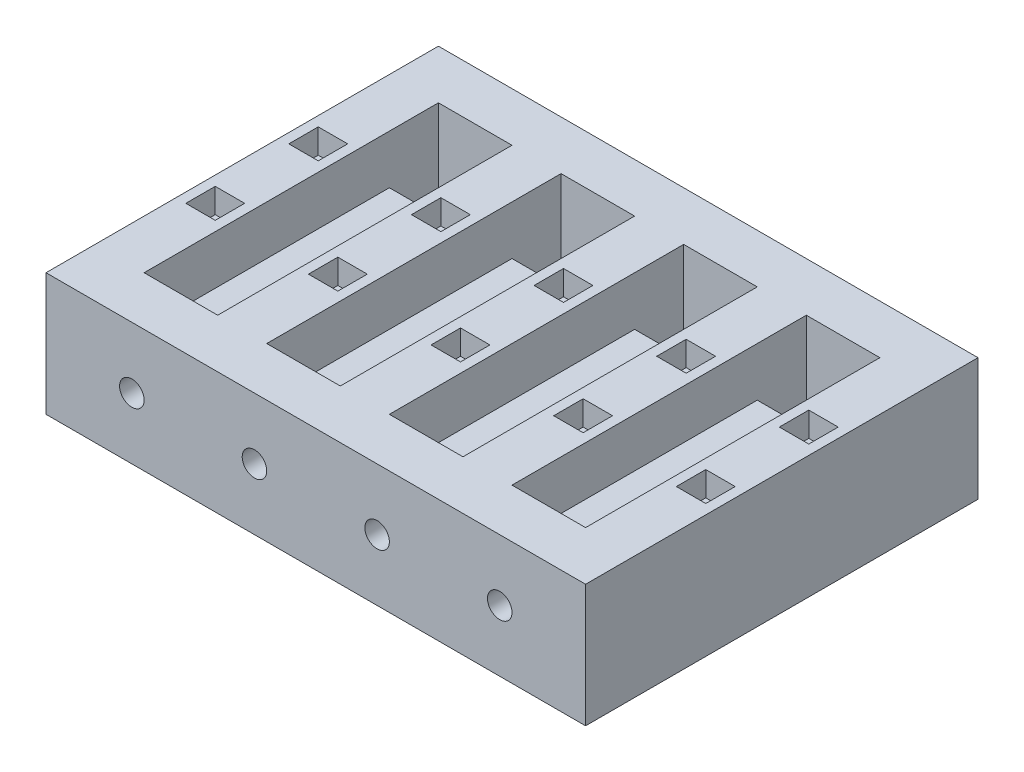
SolidWorks part; units mm, degrees
ref_plane "Front Plane" through (0, 0, 0) normal (0, 0, 1) x (1, 0, 0)
ref_plane "Top Plane" through (0, 0, 0) normal (0, 1, 0) x (1, 0, 0)
ref_plane "Right Plane" through (0, 0, 0) normal (1, 0, 0) x (0, 0, -1)
sketch "Sketch1" plane through (0, 0, 0) normal (0, 0, 1) x (1, 0, 0)
  line L1 (0, 0) -> (110, 0)
  line L2 (0, 0) -> (0, 25)
  line L3 (0, 25) -> (110, 25)
  line L4 (110, 0) -> (110, 25)
  dimension "D1" = 110
  dimension "D2" = 25
extrude "Boss-Extrude1" add sketch "Sketch1" against normal blind 80
ref_plane "Plane1" through (0, 0, -40) normal (0, 0, 1) x (1, 0, 0)
sketch "Sketch2" plane through (0, 25, 0) normal (0, 1, 0) x (1, 0, 0)
  line L1 (10, 10) -> (25, 10)
  line L2 (10, 10) -> (10, 20)
  line L3 (10, 70) -> (25, 70)
  line L4 (25, 10) -> (25, 20)
  line L16 (0, 80) -> (0, 0) construction
  line L17 (110, 0) -> (0, 0) construction
  line L18 (0, 40) -> (128.2216, 40) construction
  line L31 (10, 10) -> (35, 10) construction
  line L32 (10, 60) -> (10, 70)
  line L33 (10, 60) -> (25, 60)
  line L35 (10, 20) -> (25, 20)
  line L37 (25, 60) -> (25, 70)
  line L38 (35, 10) -> (50, 10)
  line L39 (50, 10) -> (50, 20)
  line L40 (35, 20) -> (50, 20)
  line L41 (35, 10) -> (35, 20)
  line L42 (35, 70) -> (50, 70)
  line L43 (50, 60) -> (50, 70)
  line L44 (35, 60) -> (50, 60)
  line L45 (35, 60) -> (35, 70)
  line L46 (60, 10) -> (75, 10)
  line L47 (75, 10) -> (75, 20)
  line L48 (60, 20) -> (75, 20)
  line L49 (60, 10) -> (60, 20)
  line L50 (60, 70) -> (75, 70)
  line L51 (75, 60) -> (75, 70)
  line L52 (60, 60) -> (75, 60)
  line L53 (60, 60) -> (60, 70)
  line L54 (85, 10) -> (100, 10)
  line L55 (100, 10) -> (100, 20)
  line L56 (85, 20) -> (100, 20)
  line L57 (85, 10) -> (85, 20)
  line L58 (85, 70) -> (100, 70)
  line L59 (100, 60) -> (100, 70)
  line L60 (85, 60) -> (100, 60)
  line L61 (85, 60) -> (85, 70)
  line L62 (10, 10) -> (35, 10) construction
  point P7 (0, 40)
  dimension "D1" = 15
  dimension "D2" = 60
  dimension "D4" = 10
  dimension "D5" = 10
  dimension "D6" = 25
  dimension "D7" = 10
  dimension "D8" = 10
  dimension "D9" = 25
  dimension "D3" = 4
extrude "Cut-Extrude1" cut sketch "Sketch2" against normal blind 15
sketch "Sketch4" plane through (0, 0, 0) normal (0, 0, 1) x (1, 0, 0)
  line L0 (0, 25) -> (0, 0) construction
  line L1 (110, 25) -> (0, 25) construction
  line L2 (17.5, 12.5) -> (42.5, 12.5) construction
  circle A0 centre (17.5, 12.5) radius 2.5
  circle A1 centre (42.5, 12.5) radius 2.5
  circle A2 centre (67.5, 12.5) radius 2.5
  circle A3 centre (92.5, 12.5) radius 2.5
  dimension "D3" = 5
  dimension "D1" = 17.5
  dimension "D2" = 12.5
  dimension "D5" = 25
  dimension "D4" = 4
extrude "Cut-Extrude2" cut sketch "Sketch4" against normal blind 10
mirror "Mirror1" about plane through (0, 0, -40) normal (0, 0, 1) of "Cut-Extrude2"
sketch "Sketch5" plane through (0, 25, 0) normal (0, 1, 0) x (1, 0, 0)
  line L0 (35, 20) -> (35, 60)
  line L1 (10, 20) -> (25, 20)
  line L2 (10, 20) -> (10, 60)
  line L3 (10, 60) -> (25, 60)
  line L4 (25, 20) -> (25, 60)
  line L5 (35, 20) -> (50, 20)
  line L6 (50, 20) -> (50, 60)
  line L7 (35, 60) -> (50, 60)
  line L8 (60, 20) -> (60, 60)
  line L9 (60, 20) -> (75, 20)
  line L10 (75, 20) -> (75, 60)
  line L11 (60, 60) -> (75, 60)
  line L12 (85, 20) -> (85, 60)
  line L13 (85, 20) -> (100, 20)
  line L14 (100, 20) -> (100, 60)
  line L15 (85, 60) -> (100, 60)
  line L16 (10, 20) -> (35, 20) construction
  dimension "D2" = 25
  dimension "D1" = 4
extrude "Cut-Extrude3" cut sketch "Sketch5" against normal blind 10
sketch "Sketch6" plane through (0, 25, 0) normal (0, 1, 0) x (1, 0, 0)
  line L1 (2, 47.5) -> (8, 47.5)
  line L2 (2, 47.5) -> (2, 53.5)
  line L3 (2, 53.5) -> (8, 53.5)
  line L4 (8, 47.5) -> (8, 53.5)
  line L5 (0, 80) -> (0, 0) construction
  line L6 (-13.75, 40) -> (13.75, 40) construction
  line L7 (27, 47.5) -> (27, 53.5)
  line L8 (27, 47.5) -> (33, 47.5)
  line L9 (33, 47.5) -> (33, 53.5)
  line L10 (27, 53.5) -> (33, 53.5)
  line L11 (52, 47.5) -> (52, 53.5)
  line L12 (52, 47.5) -> (58, 47.5)
  line L13 (58, 47.5) -> (58, 53.5)
  line L14 (52, 53.5) -> (58, 53.5)
  line L15 (77, 47.5) -> (77, 53.5)
  line L16 (77, 47.5) -> (83, 47.5)
  line L17 (83, 47.5) -> (83, 53.5)
  line L18 (77, 53.5) -> (83, 53.5)
  line L19 (102, 47.5) -> (102, 53.5)
  line L20 (102, 47.5) -> (108, 47.5)
  line L21 (108, 47.5) -> (108, 53.5)
  line L22 (102, 53.5) -> (108, 53.5)
  line L23 (27, 26.5) -> (27, 32.5)
  line L24 (27, 26.5) -> (33, 26.5)
  line L25 (33, 26.5) -> (33, 32.5)
  line L26 (27, 32.5) -> (33, 32.5)
  line L27 (52, 26.5) -> (52, 32.5)
  line L28 (52, 26.5) -> (58, 26.5)
  line L29 (58, 26.5) -> (58, 32.5)
  line L30 (52, 32.5) -> (58, 32.5)
  line L31 (77, 26.5) -> (77, 32.5)
  line L32 (77, 26.5) -> (83, 26.5)
  line L33 (83, 26.5) -> (83, 32.5)
  line L34 (77, 32.5) -> (83, 32.5)
  line L35 (102, 26.5) -> (102, 32.5)
  line L36 (102, 26.5) -> (108, 26.5)
  line L37 (108, 26.5) -> (108, 32.5)
  line L38 (102, 32.5) -> (108, 32.5)
  line L39 (2, 26.5) -> (2, 32.5)
  line L40 (2, 26.5) -> (8, 26.5)
  line L41 (8, 26.5) -> (8, 32.5)
  line L42 (2, 32.5) -> (8, 32.5)
  line L43 (2, 47.5) -> (27, 47.5) construction
  dimension "D1" = 6
  dimension "D2" = 6
  dimension "D3" = 2
  dimension "D4" = 7.5
  dimension "D7" = 25
  dimension "D5" = 5
  dimension "D6" = 2
extrude "Cut-Extrude4" cut sketch "Sketch6" against normal blind 5
